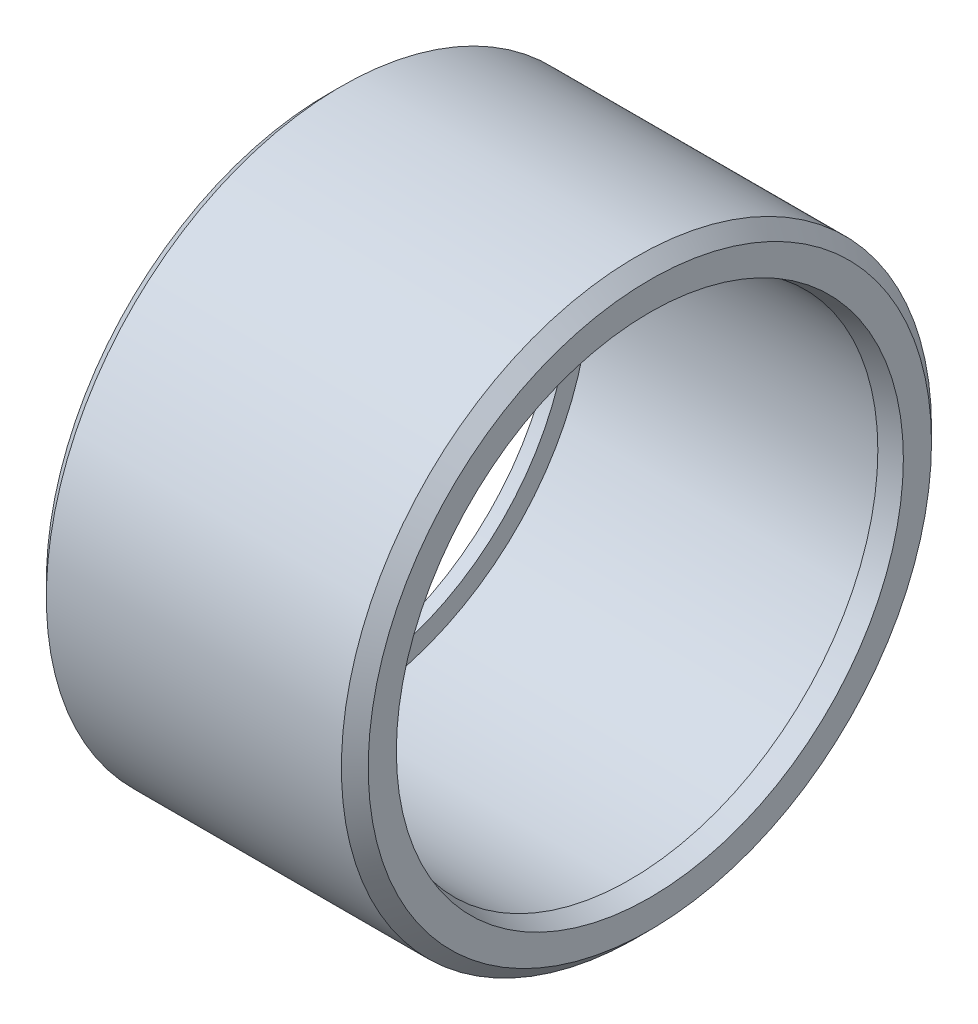
SolidWorks part; units mm, degrees
ref_plane "Plan de face" through (0, 0, 0) normal (0, 0, 1) x (1, 0, 0)
ref_plane "Plan de dessus" through (0, 0, 0) normal (0, 1, 0) x (1, 0, 0)
ref_plane "Plan de droite" through (0, 0, 0) normal (1, 0, 0) x (0, 0, -1)
sketch "Esquisse1" plane through (0, 0, 0) normal (0, 0, 1) x (1, 0, 0)
  line L0 (-22, 17) -> (-22, 21)
  line L1 (-21, 22) -> (1, 22)
  line L2 (2, 21) -> (2, 18.9019)
  line L3 (0.5, 18.5) -> (-21, 18.5)
  line L4 (-21, 18.5) -> (-21, 17)
  line L5 (-21, 17) -> (-22, 17)
  line L6 (0, 0) -> (-27.5, 0) construction
  line L7 (-22, 21) -> (-21, 22)
  line L8 (1, 22) -> (2, 21)
  line L9 (0.5, 18.5) -> (2, 18.9019)
  point P1 (-22, 22)
  point P3 (2, 22)
  dimension "D1" = 22
  dimension "D2" = 18.5
  dimension "D3" = 17
  dimension "D4" = 24
  dimension "D5" = 1
  dimension "D6" = 2
  dimension "D7" = 1.5
  dimension "D8" = 15
revolve "Révolution1" add sketch "Esquisse1" angle 360 about L6
